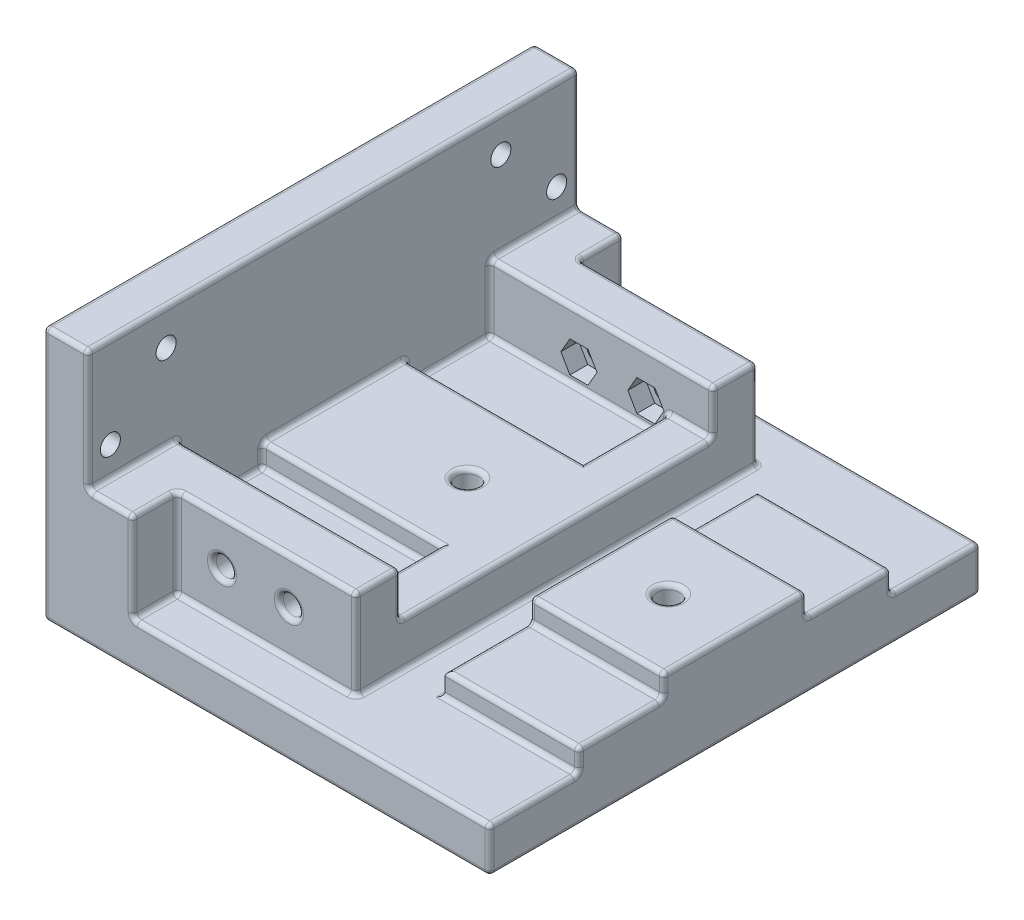
SolidWorks part; units mm, degrees
ref_plane "Front Plane" through (0, 0, 0) normal (0, 0, 1) x (1, 0, 0)
ref_plane "Top Plane" through (0, 0, 0) normal (0, 1, 0) x (1, 0, 0)
ref_plane "Right Plane" through (0, 0, 0) normal (1, 0, 0) x (0, 0, -1)
sketch "Sketch1" plane through (0, 0, 0) normal (1, 0, 0) x (0, 0, -1)
  line L1 (-38.6935, 11.3449) -> (-13.1935, 11.3449)
  line L2 (-38.6935, 11.3449) -> (-38.6935, -35.6551)
  line L3 (-38.6935, -35.6551) -> (71.3065, -35.6551)
  line L4 (71.3065, 11.3449) -> (71.3065, -35.6551)
  line L7 (45.8065, 11.3449) -> (71.3065, 11.3449)
  line L13 (-13.1935, 11.3449) -> (45.8065, 11.3449)
  circle A0 centre (-33.6935, -9.1551) radius 2.25
  circle A1 centre (-21.1935, 3.3449) radius 2.25
  circle A2 centre (66.3065, -9.1551) radius 2.25
  circle A3 centre (53.8065, 3.3449) radius 2.25
  dimension "D3" = 8
  dimension "D4" = 4.5
  dimension "D5" = 5
  dimension "D6" = 5
  dimension "D2" = 39
  dimension "D7" = 100
  dimension "D8" = 75
  dimension "D9" = 8
  dimension "D10" = 12.5
  dimension "D11" = 8
  dimension "D14" = 12.5
extrude "Boss-Extrude1" add sketch "Sketch1" along normal blind 10
sketch "Sketch2" plane through (10, 0, 0) normal (1, 0, 0) x (0, 0, -1)
  line L1 (-28.6935, -35.6551) -> (61.3065, -35.6551)
  line L5 (-38.6935, -35.6551) -> (71.3065, -35.6551) construction
  line L7 (-18.6935, -30.6551) -> (51.3065, -30.6551)
  line L10 (-28.6935, -15.6551) -> (-18.6935, -15.6551)
  line L11 (-18.6935, -30.6551) -> (-18.6935, -15.6551)
  line L14 (61.3065, -15.6551) -> (51.3065, -15.6551)
  line L15 (51.3065, -30.6551) -> (51.3065, -15.6551)
  line L16 (-28.6935, -15.6551) -> (-28.6935, -35.6551)
  line L17 (61.3065, -35.6551) -> (61.3065, -15.6551)
  line L18 (-28.6935, -35.6551) -> (-38.6935, -35.6551) construction
  line L19 (61.3065, -35.6551) -> (71.3065, -35.6551) construction
  dimension "D1" = 5
  dimension "D2" = 90
  dimension "D3" = 10
  dimension "D5" = 15
extrude "Boss-Extrude2" add sketch "Sketch2" along normal blind 50
sketch "Sketch8" plane through (10, 0, 0) normal (1, 0, 0) x (0, 0, -1)
  line L0 (-38.6935, -35.6551) -> (-28.6935, -35.6551) construction
  line L1 (-28.6935, -15.6551) -> (-38.6935, -15.6551)
  line L2 (-28.6935, -15.6551) -> (-28.6935, -35.6551)
  line L3 (-28.6935, -35.6551) -> (-38.6935, -35.6551)
  line L4 (-38.6935, -15.6551) -> (-38.6935, -35.6551)
  line L5 (61.3065, -35.6551) -> (71.3065, -35.6551) construction
  line L6 (61.3065, -15.6551) -> (71.3065, -15.6551)
  line L7 (61.3065, -15.6551) -> (61.3065, -35.6551)
  line L8 (61.3065, -35.6551) -> (71.3065, -35.6551)
  line L9 (71.3065, -15.6551) -> (71.3065, -35.6551)
  dimension "D1" = 10
extrude "Boss-Extrude3" add sketch "Sketch8" along normal blind 10
sketch "Sketch9" plane through (0, 0, 28.6935) normal (0, 0, 1) x (1, 0, 0)
  line L0 (20, -35.6551) -> (20, -15.6551) construction
  line L6 (60, -15.6551) -> (20, -15.6551) construction
  circle A0 centre (30, -25.6551) radius 2.25
  circle A1 centre (45, -25.6551) radius 2.25
  dimension "D3" = 4.5
  dimension "D1" = 10
  dimension "D2" = 10
  dimension "D4" = 15
extrude "Cut-Extrude4" cut sketch "Sketch9" against normal blind 110
sketch "Sketch10" plane through (10, 0, 0) normal (1, 0, 0) x (0, 0, -1)
  line L1 (-33.6935, -5.1136) -> (-37.1935, -7.1343)
  line L2 (-37.1935, -7.1343) -> (-37.1935, -11.1758)
  line L3 (-37.1935, -11.1758) -> (-33.6935, -13.1965)
  line L4 (-33.6935, -13.1965) -> (-30.1935, -11.1758)
  line L5 (-30.1935, -11.1758) -> (-30.1935, -7.1343)
  line L6 (-30.1935, -7.1343) -> (-33.6935, -5.1136)
  line L7 (-21.1935, 7.3864) -> (-24.6935, 5.3657)
  line L8 (-24.6935, 5.3657) -> (-24.6935, 1.3242)
  line L9 (-24.6935, 1.3242) -> (-21.1935, -0.6965)
  line L10 (-21.1935, -0.6965) -> (-17.6935, 1.3242)
  line L11 (-17.6935, 1.3242) -> (-17.6935, 5.3657)
  line L12 (-17.6935, 5.3657) -> (-21.1935, 7.3864)
  line L13 (53.8065, 7.3864) -> (50.3065, 5.3657)
  line L14 (50.3065, 5.3657) -> (50.3065, 1.3242)
  line L15 (50.3065, 1.3242) -> (53.8065, -0.6965)
  line L16 (53.8065, -0.6965) -> (57.3065, 1.3242)
  line L17 (57.3065, 1.3242) -> (57.3065, 5.3657)
  line L18 (57.3065, 5.3657) -> (53.8065, 7.3864)
  line L19 (66.3065, -5.1136) -> (62.8065, -7.1343)
  line L20 (62.8065, -7.1343) -> (62.8065, -11.1758)
  line L21 (62.8065, -11.1758) -> (66.3065, -13.1965)
  line L22 (66.3065, -13.1965) -> (69.8065, -11.1758)
  line L23 (69.8065, -11.1758) -> (69.8065, -7.1343)
  line L24 (69.8065, -7.1343) -> (66.3065, -5.1136)
  circle A0 centre (-33.6935, -9.1551) radius 3.5 construction
  circle A1 centre (-21.1935, 3.3449) radius 3.5 construction
  circle A2 centre (53.8065, 3.3449) radius 3.5 construction
  circle A3 centre (66.3065, -9.1551) radius 3.5 construction
  dimension "D1" = 7
extrude "Cut-Extrude5" [suppressed] cut sketch "Sketch10" against normal blind 4
sketch "Sketch11" plane through (0, 0, -51.3065) normal (0, 0, 1) x (1, 0, 0)
  line L1 (49.0415, -25.6551) -> (47.0207, -22.1551)
  line L2 (47.0207, -22.1551) -> (42.9793, -22.1551)
  line L3 (42.9793, -22.1551) -> (40.9585, -25.6551)
  line L4 (40.9585, -25.6551) -> (42.9793, -29.1551)
  line L5 (42.9793, -29.1551) -> (47.0207, -29.1551)
  line L6 (47.0207, -29.1551) -> (49.0415, -25.6551)
  line L7 (34.0415, -25.6551) -> (32.0207, -22.1551)
  line L8 (32.0207, -22.1551) -> (27.9793, -22.1551)
  line L9 (27.9793, -22.1551) -> (25.9585, -25.6551)
  line L10 (25.9585, -25.6551) -> (27.9793, -29.1551)
  line L11 (27.9793, -29.1551) -> (32.0207, -29.1551)
  line L12 (32.0207, -29.1551) -> (34.0415, -25.6551)
  circle A0 centre (45, -25.6551) radius 3.5 construction
  circle A1 centre (30, -25.6551) radius 3.5 construction
  dimension "D1" = 7
extrude "Cut-Extrude6" cut sketch "Sketch11" against normal blind 4
sketch "Sketch12" plane through (0, 0, 18.6935) normal (0, 0, -1) x (-1, 0, 0)
  line L1 (-40.9585, -25.6551) -> (-42.9793, -22.1551)
  line L2 (-42.9793, -22.1551) -> (-47.0207, -22.1551)
  line L3 (-47.0207, -22.1551) -> (-49.0415, -25.6551)
  line L4 (-49.0415, -25.6551) -> (-47.0207, -29.1551)
  line L5 (-47.0207, -29.1551) -> (-42.9793, -29.1551)
  line L6 (-42.9793, -29.1551) -> (-40.9585, -25.6551)
  line L7 (-25.9585, -25.6551) -> (-27.9793, -22.1551)
  line L8 (-27.9793, -22.1551) -> (-32.0207, -22.1551)
  line L9 (-32.0207, -22.1551) -> (-34.0415, -25.6551)
  line L10 (-34.0415, -25.6551) -> (-32.0207, -29.1551)
  line L11 (-32.0207, -29.1551) -> (-27.9793, -29.1551)
  line L12 (-27.9793, -29.1551) -> (-25.9585, -25.6551)
  circle A0 centre (-45, -25.6551) radius 3.5 construction
  circle A1 centre (-30, -25.6551) radius 3.5 construction
  dimension "D1" = 7
extrude "Cut-Extrude7" cut sketch "Sketch12" against normal blind 4
sketch "Sketch13" plane through (0, -30.6551, 0) normal (0, 1, 0) x (1, 0, 0)
  line L0 (60, 51.3065) -> (50, 51.3065)
  line L1 (60, 51.3065) -> (10, 51.3065) construction
  line L2 (50, 51.3065) -> (50, 32.3065)
  line L3 (50, 32.3065) -> (10, 32.3065)
  line L4 (10, 51.3065) -> (10, -18.6935) construction
  line L5 (10, 32.3065) -> (10, 0.3065)
  line L6 (10, 0.3065) -> (50, 0.3065)
  line L7 (50, 0.3065) -> (50, -18.6935)
  line L8 (60, -18.6935) -> (10, -18.6935) construction
  line L9 (50, -18.6935) -> (60, -18.6935)
  line L10 (60, -18.6935) -> (60, 51.3065)
  dimension "D1" = 32
  dimension "D2" = 10
extrude "Boss-Extrude4" add sketch "Sketch13" along normal blind 5
sketch "Sketch15" plane through (0, -35.6551, 0) normal (0, -1, 0) x (1, 0, 0)
  line L8 (0, -71.3065) -> (20, -71.3065)
  line L9 (20, -71.3065) -> (20, -61.3065)
  line L10 (20, -61.3065) -> (60, -61.3065)
  line L11 (60, -61.3065) -> (60, 28.6935)
  line L12 (60, 28.6935) -> (20, 28.6935)
  line L13 (20, 28.6935) -> (20, 38.6935)
  line L14 (20, 38.6935) -> (0, 38.6935)
  line L15 (0, 38.6935) -> (0, -71.3065)
  line L16 (0, -71.3065) -> (20, -71.3065)
  line L17 (20, -71.3065) -> (20, -61.3065)
  line L18 (20, -61.3065) -> (60, -61.3065)
  line L19 (60, -61.3065) -> (60, 28.6935)
  line L20 (60, 28.6935) -> (20, 28.6935)
  line L21 (20, 28.6935) -> (20, 38.6935)
  line L22 (20, 38.6935) -> (0, 38.6935)
  line L23 (0, 38.6935) -> (0, -71.3065)
  dimension "D1" = 0
extrude "Boss-Extrude5" add sketch "Sketch15" along normal blind 10
sketch "Sketch17" plane through (0, 0, 28.6935) normal (0, 0, 1) x (1, 0, 0)
  line L1 (20, -35.6551) -> (60, -35.6551)
  line L5 (20, -15.6551) -> (20, -45.6551)
  line L6 (20, -45.6551) -> (60, -45.6551)
  line L7 (60, -45.6551) -> (60, -15.6551)
  line L8 (60, -15.6551) -> (20, -15.6551)
  line L9 (20, -35.6551) -> (20, -45.6551)
  line L10 (20, -45.6551) -> (60, -45.6551)
  line L11 (60, -45.6551) -> (60, -35.6551)
  dimension "D2" = 10
  dimension "D1" = 0
extrude "Boss-Extrude6" add sketch "Sketch17" along normal blind 10
sketch "Sketch18" plane through (0, 0, -61.3065) normal (0, 0, -1) x (-1, 0, 0)
  line L0 (-60, -35.6551) -> (-20, -35.6551)
  line L4 (-60, -15.6551) -> (-60, -45.6551)
  line L5 (-60, -45.6551) -> (-20, -45.6551)
  line L6 (-20, -45.6551) -> (-20, -15.6551)
  line L7 (-20, -15.6551) -> (-60, -15.6551)
  line L8 (-60, -35.6551) -> (-60, -45.6551)
  line L9 (-60, -45.6551) -> (-20, -45.6551)
  line L10 (-20, -45.6551) -> (-20, -35.6551)
  dimension "D2" = 10
  dimension "D1" = 0
extrude "Boss-Extrude7" add sketch "Sketch18" along normal blind 10
sketch "Sketch19" plane through (60, 0, 0) normal (1, 0, 0) x (0, 0, -1)
  line L0 (-28.6935, -35.6551) -> (61.3065, -35.6551)
  line L12 (51.3065, -25.6551) -> (-18.6935, -25.6551)
  line L13 (-18.6935, -25.6551) -> (-18.6935, -15.6551)
  line L14 (-18.6935, -15.6551) -> (-28.6935, -15.6551)
  line L15 (-28.6935, -15.6551) -> (-28.6935, -35.6551)
  line L16 (-28.6935, -35.6551) -> (-38.6935, -35.6551)
  line L17 (-38.6935, -35.6551) -> (-38.6935, -45.6551)
  line L18 (-38.6935, -45.6551) -> (71.3065, -45.6551)
  line L19 (71.3065, -45.6551) -> (71.3065, -35.6551)
  line L20 (71.3065, -35.6551) -> (61.3065, -35.6551)
  line L21 (61.3065, -35.6551) -> (61.3065, -15.6551)
  line L22 (61.3065, -15.6551) -> (51.3065, -15.6551)
  line L23 (51.3065, -15.6551) -> (51.3065, -25.6551)
  line L28 (-28.6935, -35.6551) -> (-38.6935, -35.6551)
  line L29 (-38.6935, -35.6551) -> (-38.6935, -45.6551)
  line L30 (-38.6935, -45.6551) -> (71.3065, -45.6551)
  line L31 (71.3065, -45.6551) -> (71.3065, -35.6551)
  line L32 (71.3065, -35.6551) -> (61.3065, -35.6551)
  dimension "D1" = 0
extrude "Boss-Extrude8" add sketch "Sketch19" along normal blind 40
sketch "Sketch21" plane through (0, -35.6551, 0) normal (0, 1, 0) x (1, 0, 0)
  line L1 (70, -18.6935) -> (100, -18.6935)
  line L2 (100, 71.3065) -> (100, -38.6935) construction
  line L6 (100, -18.6935) -> (100, 51.3065)
  line L7 (100, 51.3065) -> (70, 51.3065)
  line L8 (70, 51.3065) -> (70, -18.6935)
  line L9 (60, 51.3065) -> (50, 51.3065) construction
  line L10 (50, -18.6935) -> (60, -18.6935) construction
  line L11 (60, -18.6935) -> (60, 51.3065) construction
  point P14 (0, 0)
  point P15 (0, 0)
  dimension "D1" = 30
extrude "Boss-Extrude9" add sketch "Sketch21" along normal blind 5
sketch "Sketch22" plane through (0, -30.6551, 0) normal (0, 1, 0) x (1, 0, 0)
  line L0 (70, 32.3065) -> (70, 0.3065)
  line L1 (70, 51.3065) -> (70, -18.6935) construction
  line L2 (70, 0.3065) -> (100, 0.3065)
  line L3 (100, -18.6935) -> (100, 51.3065) construction
  line L4 (100, 0.3065) -> (100, 32.3065)
  line L5 (100, 32.3065) -> (70, 32.3065)
  line L7 (50, 32.3065) -> (10, 32.3065) construction
  line L8 (10, 0.3065) -> (50, 0.3065) construction
  point P12 (0, 0)
  point P14 (0, 0)
extrude "Boss-Extrude10" add sketch "Sketch22" along normal blind 5
hole_wizard "1/4-20 Tapped Hole1" positions "3DSketch2" profile "Sketch25" tap size "1/4-20" standard "ANSI Inch"
sketch3d "3DSketch2"
  point P0 (85, -25.6551, -16.3065)
  point P44 (0, 0, 0)
  point P45 (0, 0, 0)
  point P46 (0, 0, 0)
sketch "Sketch25" plane through (85, -25.6551, -16.3065) normal (1, 0, 0) x (0, 0, 1)
  line L0 (0, 0) -> (0, 21.5338)
  line L1 (0, 21.5338) -> (2.5527, 20)
  line L2 (2.5527, 20) -> (2.5527, 0)
  line L5 (2.5527, 0) -> (0, 0)
  line L10 (0, 21.5338) -> (-2.5527, 20) construction
  line L11 (0, -6.35) -> (0, 107.95) construction
  dimension "Tap Drill Dia." = 5.1054
  dimension "Tap Drill Depth" = 20
  dimension "Drill Angle" = 118
cosmetic thread "Hole Thread1" parameters "D1"=12.7, "D2"=6.35
hole_wizard "1/4-20 Tapped Hole2" positions "3DSketch3" profile "Sketch26" tap size "1/4-20" standard "ANSI Inch"
sketch3d "3DSketch3"
  line L0 (50, -25.6551, -32.3065) -> (10, -25.6551, -32.3065) construction
  line L3 (10, -25.6551, -0.3065) -> (50, -25.6551, -0.3065) construction
  line L4 (10, -25.6551, -32.3065) -> (10, -25.6551, -0.3065) construction
  point P0 (40, -25.6551, -16.3065)
  dimension "D1" = 16
  dimension "D2" = 16
  dimension "D3" = 30
sketch "Sketch26" plane through (40, -25.6551, -16.3065) normal (1, 0, 0) x (0, 0, 1)
  line L0 (0, 0) -> (0, 21.5338)
  line L1 (0, 21.5338) -> (2.5527, 20)
  line L2 (2.5527, 20) -> (2.5527, 0)
  line L5 (2.5527, 0) -> (0, 0)
  line L10 (0, 21.5338) -> (-2.5527, 20) construction
  line L11 (0, -6.35) -> (0, 107.95) construction
  dimension "Tap Drill Dia." = 5.1054
  dimension "Tap Drill Depth" = 20
  dimension "Drill Angle" = 118
cosmetic thread "Hole Thread2" parameters "D1"=12.7, "D2"=6.35
fillet "Fillet5" radius 1 96 edges at (0, 3.3449, -56.0565) (0, -9.1551, -68.5565) (0, 3.3449, 18.9435) (0, -9.1551, 31.4435) (0, -17.1551, -71.3065) (0, 11.3449, -16.3065) (0, -17.1551, 38.6935) (10, -2.1551, -71.3065) (10, -23.1551, -51.3065) (10, -23.1551, 18.6935) (5, 11.3449, 38.6935) (5, 11.3449, -71.3065) (10, 11.3449, -16.3065) (15, -15.6551, -71.3065) (20, -15.6551, -66.3065) (40, -15.6551, -61.3065) (35, -15.6551, -51.3065) (10, -15.6551, -61.3065) (35, -15.6551, 18.6935) (40, -15.6551, 28.6935) (20, -15.6551, 33.6935) (15, -15.6551, 38.6935) (10, -15.6551, 28.6935) (60, -15.6551, 23.6935) (60, -20.6551, 18.6935) (60, -20.6551, -51.3065) (60, -15.6551, -56.3065) (60, -25.6551, -61.3065) (60, -25.6551, 28.6935) (10, -2.1551, 38.6935) (30, -30.6551, -51.3065) (30, -30.6551, 18.6935) (10, -30.6551, -41.8065) (10, -30.6551, 9.1935) (20, -25.6551, 38.6935) (20, -25.6551, 28.6935) (20, -25.6551, -61.3065) (20, -25.6551, -71.3065) (32.25, -25.6551, -61.3065) (47.25, -25.6551, -61.3065) (32.25, -25.6551, 28.6935) (47.25, -25.6551, 28.6935) (60, -25.6551, -16.3065) (50, -28.1551, -51.3065) (50, -28.1551, 18.6935) (30, -25.6551, -32.3065) (50, -25.6551, -41.8065) (50, -25.6551, 9.1935) (30, -25.6551, -0.3065) (40, -35.6551, 28.6935) (40, -35.6551, -61.3065) (60, -35.6551, -16.3065) (0, -45.6551, -16.3065) (70, -28.1551, -32.3065) (70, -28.1551, -0.3065) (50, -45.6551, 38.6935) (100, -40.6551, -71.3065) (100, -45.6551, -16.3065) (100, -40.6551, 38.6935) (100, -33.1551, 18.6935) (100, -28.1551, -0.3065) (100, -28.1551, -32.3065) (100, -33.1551, -51.3065) (100, -25.6551, -16.3065) (85, -25.6551, -0.3065) (70, -25.6551, -16.3065) (85, -25.6551, -32.3065) (85, -25.6551, -13.7538) (70, -30.6551, -41.8065) (85, -30.6551, -51.3065) (100, -30.6551, -41.8065) (85, -30.6551, -32.3065) (100, -30.6551, 9.1935) (85, -30.6551, 18.6935) (70, -30.6551, 9.1935) (85, -30.6551, -0.3065) (100, -35.6551, 28.6935) (85, -35.6551, 18.6935) (85, -35.6551, -51.3065) (60, -35.6551, -71.3065) (60, -35.6551, 38.6935) (20, -35.6551, 33.6935) (20, -35.6551, -66.3065) (100, -35.6551, -61.3065) (70, -35.6551, -16.3065) (50, -45.6551, -71.3065) (50, -30.6551, 9.1935) (30, -30.6551, -0.3065) (30, -30.6551, -32.3065) (50, -30.6551, -41.8065) (10, -28.1551, -0.3065) (10, -28.1551, -32.3065) (55, -25.6551, 18.6935) (10, -25.6551, -16.3065) (55, -25.6551, -51.3065) (40, -25.6551, -13.7538)
